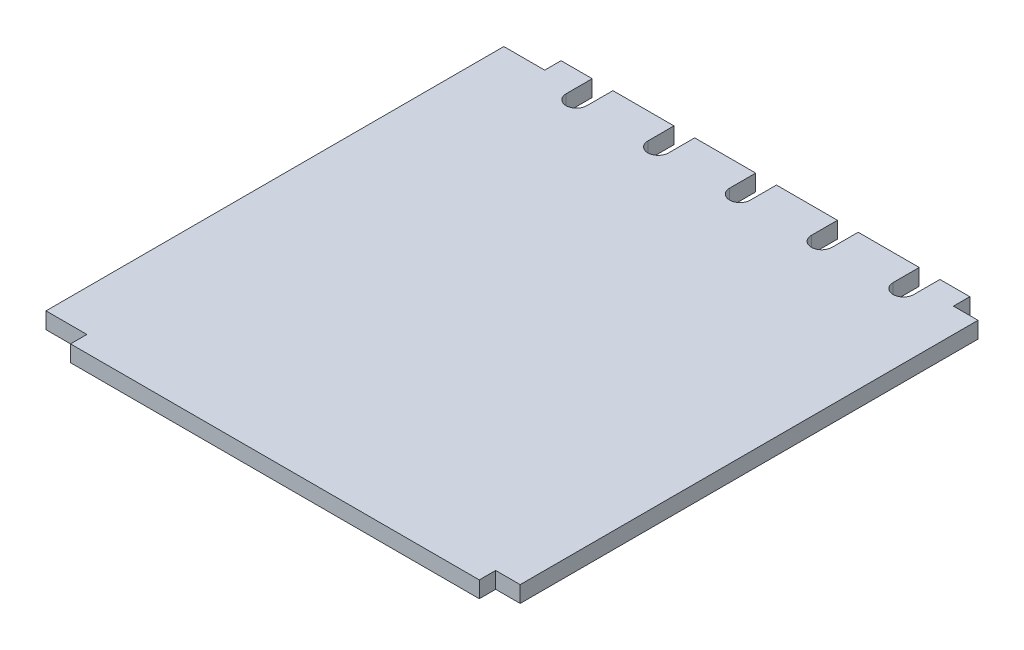
SolidWorks part; units mm, degrees
ref_plane "Front Plane" through (0, 0, 0) normal (0, 0, 1) x (1, 0, 0)
ref_plane "Top Plane" through (0, 0, 0) normal (0, 1, 0) x (1, 0, 0)
ref_plane "Right Plane" through (0, 0, 0) normal (1, 0, 0) x (0, 0, -1)
sketch "Sketch1" plane through (0, 0, 0) normal (0, 1, 0) x (1, 0, 0)
  line L0 (-71.12, 71.12) -> (-63.5, 71.12)
  line L1 (-63.5, -76.2) -> (63.5, -76.2)
  line L2 (-76.2, -63.5) -> (-76.2, 63.5)
  line L3 (-63.5, 76.2) -> (-53.822, 76.2)
  line L4 (-76.2, -63.5) -> (-76.2, -71.12)
  line L5 (-76.2, -76.2) -> (-71.12, -71.12) construction
  line L6 (-50.6021, 76.2) -> (-50.6021, 68.0905) construction
  line L7 (71.12, -71.12) -> (71.12, -63.5)
  line L8 (-71.12, -71.12) -> (-63.5, -71.12)
  line L9 (-76.2, 63.5) -> (-76.2, 71.12)
  line L10 (-63.5, 76.2) -> (-63.5, 71.12)
  line L11 (-76.2, 71.12) -> (-71.12, 71.12)
  line L12 (-76.2, -71.12) -> (-71.12, -71.12)
  line L13 (63.5, -76.2) -> (63.5, -71.12)
  line L14 (0, 0) -> (0, 23.5645) construction
  line L15 (-63.5, -76.2) -> (-63.5, -71.12)
  line L18 (63.5, 76.2) -> (63.5, 71.12)
  line L20 (-76.2, 76.2) -> (76.2, 76.2) construction
  line L21 (-76.2, -76.2) -> (-76.2, 76.2) construction
  line L22 (63.5, 71.12) -> (71.12, 71.12)
  line L23 (-71.12, -71.12) -> (-71.12, 71.12) construction
  line L24 (63.5, -71.12) -> (71.12, -71.12)
  line L25 (-71.12, 71.12) -> (71.12, 71.12) construction
  line L26 (-76.2, -76.2) -> (76.2, -76.2) construction
  line L27 (71.12, 63.5) -> (71.12, 71.12)
  line L28 (-71.12, -71.12) -> (71.12, -71.12) construction
  line L29 (76.2, -76.2) -> (76.2, 76.2) construction
  line L30 (-47.3823, 76.2) -> (-47.3823, 68.0905)
  line L31 (71.12, -71.12) -> (71.12, 71.12) construction
  line L32 (-53.822, 76.2) -> (-53.822, 68.0905)
  line L33 (-25.2021, 76.2) -> (-25.2021, 68.0905) construction
  line L34 (-21.9823, 76.2) -> (-21.9823, 68.0905)
  line L35 (-28.422, 76.2) -> (-28.422, 68.0905)
  line L36 (0.1979, 76.2) -> (0.1979, 68.0905) construction
  line L37 (3.4177, 76.2) -> (3.4177, 68.0905)
  line L38 (-3.022, 76.2) -> (-3.022, 68.0905)
  line L39 (25.5979, 76.2) -> (25.5979, 68.0905) construction
  line L40 (28.8177, 76.2) -> (28.8177, 68.0905)
  line L41 (22.378, 76.2) -> (22.378, 68.0905)
  line L42 (50.9979, 76.2) -> (50.9979, 68.0905) construction
  line L43 (54.2177, 76.2) -> (54.2177, 68.0905)
  line L44 (47.778, 76.2) -> (47.778, 68.0905)
  line L45 (-47.3823, 76.2) -> (-28.422, 76.2)
  line L46 (-21.9823, 76.2) -> (-3.022, 76.2)
  line L47 (3.4177, 76.2) -> (22.378, 76.2)
  line L48 (28.8177, 76.2) -> (47.778, 76.2)
  line L49 (54.2177, 76.2) -> (63.5, 76.2)
  line L50 (71.12, -63.5) -> (71.12, 63.5)
  arc A1 (-53.822, 68.0905) -> (-47.3823, 68.0905) centre (-50.6021, 68.0905) ccw
  arc A3 (-28.422, 68.0905) -> (-21.9823, 68.0905) centre (-25.2021, 68.0905) ccw
  arc A5 (-3.022, 68.0905) -> (3.4177, 68.0905) centre (0.1979, 68.0905) ccw
  arc A7 (22.378, 68.0905) -> (28.8177, 68.0905) centre (25.5979, 68.0905) ccw
  arc A9 (47.778, 68.0905) -> (54.2177, 68.0905) centre (50.9979, 68.0905) ccw
  point P0 (0, 0)
  point P30 (-50.6021, 72.1452)
  point P38 (-25.2021, 72.1452)
  point P45 (0.1979, 72.1452)
  point P52 (25.5979, 72.1452)
  point P59 (50.9979, 72.1452)
  dimension "D4" = 12.7
  dimension "D3" = 5.08
extrude "Boss-Extrude1" add sketch "Sketch1" along normal blind 5.08
